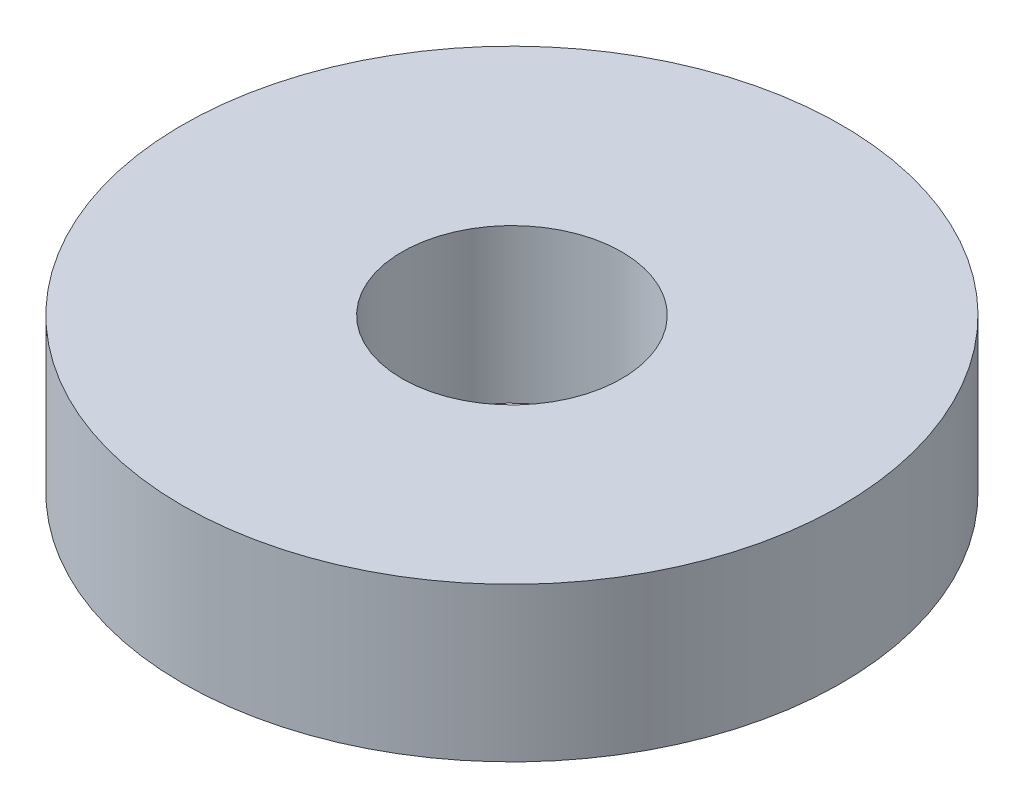
SolidWorks part; units mm, degrees
material "聚脂树脂"
ref_plane "前视基准面" through (0, 0, 0) normal (0, 0, 1) x (1, 0, 0)
ref_plane "上视基准面" through (0, 0, 0) normal (0, 1, 0) x (1, 0, 0)
ref_plane "右视基准面" through (0, 0, 0) normal (1, 0, 0) x (0, 0, -1)
other "Configuration Table"
sketch "草图1" plane through (0, 0, 0) normal (0, 1, 0) x (1, 0, 0)
  circle A0 centre (0, 0) radius 2.5
  circle A1 centre (0, 0) radius 7.5
  dimension "D1" = 5
  dimension "D2" = 15
extrude "凸台-拉伸1" add sketch "草图1" along normal blind 3.5
